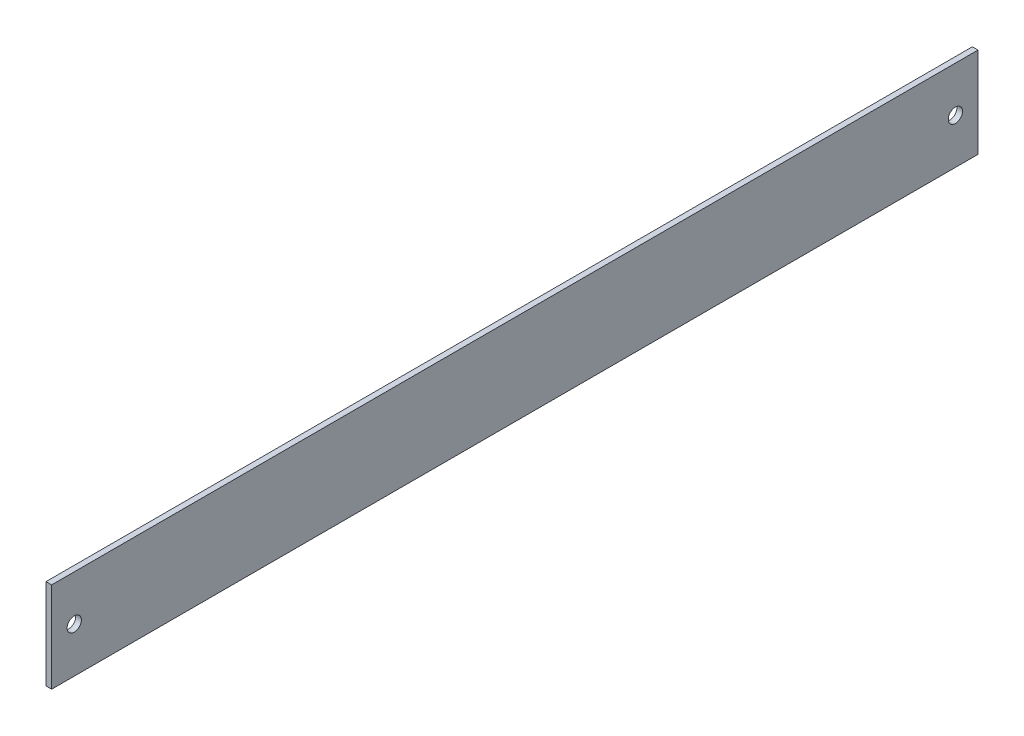
SolidWorks part; units mm, degrees
ref_plane "Front Plane" through (0, 0, 0) normal (0, 0, 1) x (1, 0, 0)
ref_plane "Top Plane" through (0, 0, 0) normal (0, 1, 0) x (1, 0, 0)
ref_plane "Right Plane" through (0, 0, 0) normal (1, 0, 0) x (0, 0, -1)
sketch "Sketch1" plane through (0, 0, 0) normal (1, 0, 0) x (0, 0, -1)
  line L1 (0, 0) -> (520.7, 0)
  line L2 (0, 0) -> (0, 50.8)
  line L3 (0, 50.8) -> (520.7, 50.8)
  line L4 (520.7, 0) -> (520.7, 50.8)
  circle A0 centre (12.7, 25.4) radius 4
  circle A1 centre (508, 25.4) radius 4
  dimension "D3" = 8
  dimension "D1" = 50.8
  dimension "D2" = 520.7
  dimension "D4" = 25.4
  dimension "D5" = 12.7
  dimension "D6" = 12.7
  dimension "D7" = 508
extrude "Boss-Extrude2" add sketch "Sketch1" along normal blind 3.175
equation "\"RailThickness\"= .125in'Spec"
equation "\"VSWidth\"= 1.25in'Spec"
equation "\"StepperHolePadSize\"= \"StepperHoleDiameter\""
equation "\"D1@Sketch1\" = \"LowerRailHeight\""
equation "\"D2@Sketch1\" = \"FrontOrBackRailLength\""
equation "\"FrameFastenerHoleDiameter\"= 8mm"
equation "\"D3@Sketch1\"=\"FrameFastenerHoleDiameter\""
equation "\"D4@Sketch1\" = \"LowerRailHeight\" / 2"
equation "\"D5@Sketch1\"=\"FrameFastenerHoleOffsetFromEdge\""
equation "\"D6@Sketch1\"=\"FrameFastenerHoleOffsetFromEdge\""
equation "\"D1@Boss-Extrude2\"=\"RailThickness\""
equation "\"FrameFastenerHoleOffsetFromEdge\"= \"VSWidth\" / 2 - \"GapBetweenVerticalSupportsAndRails\" / 2"
equation "\"LowerRailHeight\"= 2.0in"
equation "\"FrontOrBackRailLength\"= 20.5in"
equation "\"GapBetweenVerticalSupportsAndRails\"= \"RailThickness\" * 2"
